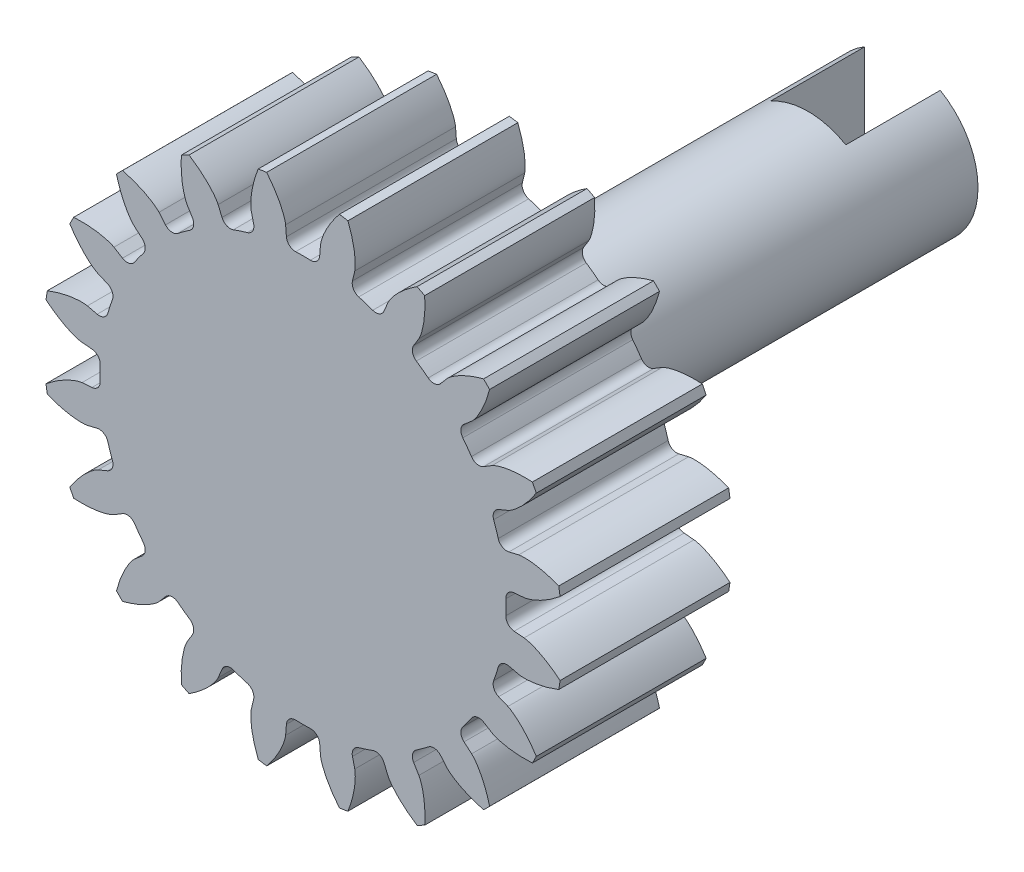
SolidWorks part; units mm, degrees
ref_plane "Front Plane" through (0, 0, 0) normal (0, 0, 1) x (1, 0, 0)
ref_plane "Top Plane" through (0, 0, 0) normal (0, 1, 0) x (1, 0, 0)
ref_plane "Right Plane" through (0, 0, 0) normal (1, 0, 0) x (0, 0, -1)
ref_axis "Gear Axis" through (0, 0, -0.4501) along (0, 0, 1)
sketch "Blank Sketch" plane through (0, 0, 0) normal (0, 0, 1) x (1, 0, 0)
  circle A0 centre (0, 0) radius 13.75
  dimension "OD" = 27.5
extrude "Blank" add sketch "Blank Sketch" along normal blind 9
sketch "Tooth Space Sketch" plane through (0, 0, 0) normal (0, 0, 1) x (1, 0, 0)
  line L0 (11.7099, 0.9227) -> (11.1803, 0.881)
  line L1 (11.7099, -0.9227) -> (11.1803, -0.881)
  line L2 (14.6961, 3.0042) -> (14.6961, -3.0042)
  arc A0 (11.1803, 0.881) -> (10.7429, 0.3902) centre (11.2176, 0.4075) ccw
  arc A1 (10.7429, -0.3902) -> (11.1803, -0.881) centre (11.2176, -0.4075) ccw
  arc A2 (10.7429, -0.3902) -> (10.7429, 0.3902) centre (0, 0) ccw
  spline S0 degree 4 poles (11.7099, 0.9227) (11.7153, 0.9232) (11.7306, 0.925) (11.7593, 0.9294) (11.806, 0.9382) (11.8651, 0.9517) (11.9409, 0.9719) (12.0295, 0.999) (12.1261, 1.0323) (12.2301, 1.0723) (12.3329, 1.1155) (12.4344, 1.1617) (12.5347, 1.2105) (12.6549, 1.2727) (12.7975, 1.3519) (12.9615, 1.4507) (13.1443, 1.5703) (13.3269, 1.7) (13.5034, 1.834) (13.678, 1.9766) (13.8441, 2.1196) (14.0125, 2.2754) (14.1658, 2.4228) (14.3326, 2.5956) (14.4659, 2.7374) (14.6362, 2.9324) (14.7351, 3.0499) (14.8489, 3.1902) (14.8984, 3.2539) (14.9289, 3.293) knots 0 0 0 0 0 0.005377 0.015084 0.028532 0.04661 0.064855 0.092111 0.119476 0.146842 0.174209 0.201575 0.228941 0.256307 0.307035 0.361767 0.4165 0.471232 0.525964 0.580697 0.635429 0.690161 0.744894 0.799626 0.854358 0.909091 0.954545 1 1 1 1 1 construction
  spline S1 degree 4 poles (11.7099, 0.9227) (11.7153, 0.9232) (11.7306, 0.925) (11.7593, 0.9294) (11.806, 0.9382) (11.8651, 0.9517) (11.9409, 0.9719) (12.0295, 0.999) (12.1261, 1.0323) (12.2301, 1.0723) (12.3329, 1.1155) (12.4344, 1.1617) (12.5347, 1.2105) (12.6549, 1.2727) (12.7975, 1.3519) (12.9615, 1.4507) (13.1443, 1.5703) (13.3269, 1.7) (13.5034, 1.834) (13.678, 1.9766) (13.8441, 2.1196) (14.0125, 2.2754) (14.1658, 2.4228) (14.3326, 2.5956) (14.4659, 2.7374) (14.5992, 2.8901) (14.6635, 2.9654) (14.6961, 3.0042) knots 0 0 0 0 0 0.005377 0.015084 0.028532 0.04661 0.064855 0.092111 0.119476 0.146842 0.174209 0.201575 0.228941 0.256307 0.307035 0.361767 0.4165 0.471232 0.525964 0.580697 0.635429 0.690161 0.744894 0.799626 0.854358 0.909091 0.909091 0.909091 0.909091 0.909091
  spline S2 degree 4 poles (11.7099, -0.9227) (11.7153, -0.9232) (11.7306, -0.925) (11.7593, -0.9294) (11.806, -0.9382) (11.8651, -0.9517) (11.9409, -0.9719) (12.0295, -0.999) (12.1261, -1.0323) (12.2301, -1.0723) (12.3329, -1.1155) (12.4344, -1.1617) (12.5347, -1.2105) (12.6549, -1.2727) (12.7975, -1.3519) (12.9615, -1.4507) (13.1443, -1.5703) (13.3269, -1.7) (13.5034, -1.834) (13.678, -1.9766) (13.8441, -2.1196) (14.0125, -2.2754) (14.1658, -2.4228) (14.3326, -2.5956) (14.4659, -2.7374) (14.6362, -2.9324) (14.7351, -3.0499) (14.8489, -3.1902) (14.8984, -3.2539) (14.9289, -3.293) knots 0 0 0 0 0 0.005377 0.015084 0.028532 0.04661 0.064855 0.092111 0.119476 0.146842 0.174209 0.201575 0.228941 0.256307 0.307035 0.361767 0.4165 0.471232 0.525964 0.580697 0.635429 0.690161 0.744894 0.799626 0.854358 0.909091 0.954545 1 1 1 1 1 construction
  spline S3 degree 4 poles (11.7099, -0.9227) (11.7153, -0.9232) (11.7306, -0.925) (11.7593, -0.9294) (11.806, -0.9382) (11.8651, -0.9517) (11.9409, -0.9719) (12.0295, -0.999) (12.1261, -1.0323) (12.2301, -1.0723) (12.3329, -1.1155) (12.4344, -1.1617) (12.5347, -1.2105) (12.6549, -1.2727) (12.7975, -1.3519) (12.9615, -1.4507) (13.1443, -1.5703) (13.3269, -1.7) (13.5034, -1.834) (13.678, -1.9766) (13.8441, -2.1196) (14.0125, -2.2754) (14.1658, -2.4228) (14.3326, -2.5956) (14.4659, -2.7374) (14.5992, -2.8901) (14.6635, -2.9654) (14.6961, -3.0042) knots 0 0 0 0 0 0.005377 0.015084 0.028532 0.04661 0.064855 0.092111 0.119476 0.146842 0.174209 0.201575 0.228941 0.256307 0.307035 0.361767 0.4165 0.471232 0.525964 0.580697 0.635429 0.690161 0.744894 0.799626 0.854358 0.909091 0.909091 0.909091 0.909091 0.909091
  dimension "Root" = 10.75
  dimension "Fillet" = 0.475
extrude "Tooth Space" cut sketch "Tooth Space Sketch" against normal through all both and the other way through all both
pattern_circular "Teeth" count 20 over 360 about axis through (0, 0, -0.4501) along (0, 0, 1) of "Tooth Space"
sketch "Bore Sketch" plane through (0, 0, 0) normal (0, 0, 1) x (1, 0, 0)
  circle A0 centre (0, 0) radius 4
  dimension "Bore" = 8
extrude "Bore" cut sketch "Bore Sketch" against normal through all both and the other way through all both
sketch "Sketch1" plane through (0, 0, 9) normal (0, 0, 1) x (1, 0, 0)
  circle A0 centre (0, 0) radius 4 construction
  circle A1 centre (0, 0) radius 4
extrude "Boss-Extrude1" add sketch "Sketch1" against normal blind 55
ref_plane "Plane1" through (0, 0, -17.75) normal (0, 0, -1) x (-1, 0, 0)
split "Split1" trim tools "Plane1" bodies to split 105 resulting bodies 106
sketch "Sketch2" plane through (0, 0, -17.75) normal (0, 0, -1) x (-1, 0, 0)
  line L0 (2, 3.4641) -> (2, -3.4641)
  line L1 (-2, 3.4641) -> (-2, -3.4641)
  circle A0 centre (0, 0) radius 4 construction
  arc A1 (-2, 3.4641) -> (-2, -3.4641) centre (0, 0) ccw
  arc A2 (2, 3.4641) -> (-2, 3.4641) centre (0, 0) ccw construction
  arc A3 (-2, -3.4641) -> (2, -3.4641) centre (0, 0) ccw construction
  arc A4 (2, -3.4641) -> (2, 3.4641) centre (0, 0) ccw
  dimension "D1" = 2
  dimension "2" = 2
extrude "Boss-Extrude2" add sketch "Sketch2" along normal blind 5
equation "\"No. of Teeth\"= 20"
equation "\"Module\"= 1.25"
equation "\"Bore Diameter\"= 8"
equation "\"Pressure Angle\"= 20"
equation "\"Outer Diameter\"= ( \"No. of Teeth\" + 2 ) * \"Module\""
equation "\"Pitch Diameter\"= \"No. of Teeth\" * \"Module\""
equation "\"Backlash\"= 0.3 * \"Module\""
equation "\"Arc Length\"= ( ( \"Module\" * pi ) / 2 + \"Backlash\" )"
equation "\"Fillet Radius\"= 0.38 * \"Module\""
equation "\"Tooth Depth\"= IIF ( \"Module\" <= 1.25 , \"Module\" * 2.4 , \"Module\" * 2.25 )"
equation "\"Face Width\"= 9"
equation "\"Root Diameter\"= \"Outer Diameter\" - 2 * \"Tooth Depth\""
equation "\"Base Diameter\"= \"Pitch Diameter\" * cos ( \"Pressure Angle\" )"
equation "\"Base Radius\"= \"Base Diameter\" / 2"
equation "\"Tooth Thickness\"= \"Module\" * pi - \"Arc Length\""
equation "\"Half Space Angle\"= ( \"Arc Length\" / \"Pitch Diameter\" ) * 180 / pi"
equation "\"Involute Fn\"= tan ( \"Pressure Angle\" ) - \"Pressure Angle\" * pi / 180"
equation "\"Flank Offset\"= \"Arc Length\" / \"Pitch Diameter\" - \"Involute Fn\""
equation "\"Tip Cap Diameter\"= \"Outer Diameter\" + 2 * \"Module\""
equation "\"Flank Start Diameter\"= IIF ( \"Base Diameter\" >= ( \"Root Diameter\" + 3 * \"Fillet Radius\" ) , \"Base Diameter\" , \"Root Diameter\" + 3 * \"Fillet Radius\" )"
equation "\"Involute t1\"= ( abs ( ( \"Flank Start Diameter\" / \"Base Diameter\" ) ^ 2 - 1 ) ) ^ 0.5"
equation "\"Involute t2\"= ( abs ( ( \"Tip Cap Diameter\" / \"Base Diameter\" ) ^ 2 - 1 ) ) ^ 0.5"
equation "\"Flank Arc Radius\"= ( \"Pitch Diameter\" / 2 ) * sin ( \"Pressure Angle\" )"
equation "\"Flank Centre Angle\"= \"Half Space Angle\" + \"Pressure Angle\""
equation "\"OD@Blank Sketch\"= \"Outer Diameter\""
equation "\"Width@Blank\"= \"Face Width\""
equation "\"Root@Tooth Space Sketch\"= \"Root Diameter\" / 2"
equation "\"Fillet@Tooth Space Sketch\"= \"Fillet Radius\""
equation "\"Count@Teeth\"= \"No. of Teeth\""
equation "\"Bore@Bore Sketch\"= \"Bore Diameter\""
